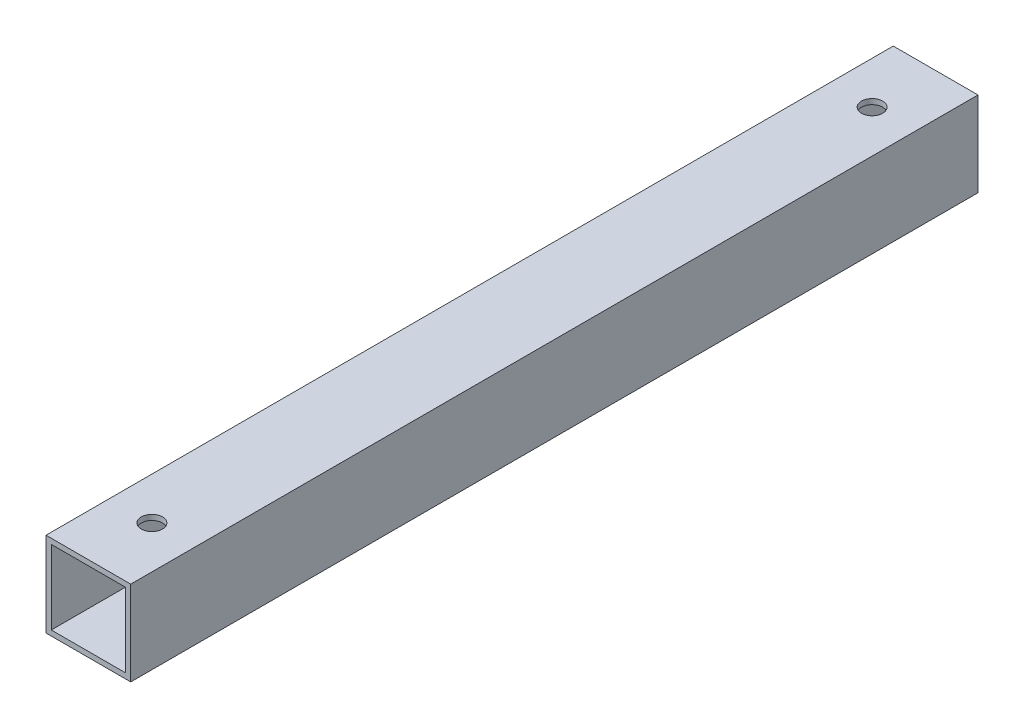
SolidWorks part; units mm, degrees
ref_plane "Front Plane" through (0, 0, 0) normal (0, 0, 1) x (1, 0, 0)
ref_plane "Top Plane" through (0, 0, 0) normal (0, 1, 0) x (1, 0, 0)
ref_plane "Right Plane" through (0, 0, 0) normal (1, 0, 0) x (0, 0, -1)
sketch "Sketch1" plane through (0, 0, 0) normal (0, 0, 1) x (1, 0, 0)
  line L1 (-11.1125, -11.1125) -> (11.1125, -11.1125)
  line L2 (-11.1125, -11.1125) -> (-11.1125, 11.1125)
  line L3 (-11.1125, 11.1125) -> (11.1125, 11.1125)
  line L4 (11.1125, -11.1125) -> (11.1125, 11.1125)
  line L5 (-11.1125, -11.1125) -> (11.1125, 11.1125) construction
  line L6 (-11.1125, 11.1125) -> (11.1125, -11.1125) construction
  line L7 (-12.7, -12.7) -> (12.7, -12.7)
  line L8 (-12.7, -12.7) -> (-12.7, 12.7)
  line L9 (-12.7, 12.7) -> (12.7, 12.7)
  line L10 (12.7, -12.7) -> (12.7, 12.7)
  line L11 (-12.7, -12.7) -> (12.7, 12.7) construction
  line L12 (-12.7, 12.7) -> (12.7, -12.7) construction
  point P0 (0, 0)
  point P6 (0, 0)
  dimension "D1" = 25.4
  dimension "D2" = 1.5875
extrude "Boss-Extrude1" add sketch "Sketch1" along normal blind 254
sketch "Sketch2" plane through (0, 12.7, 0) normal (0, 1, 0) x (1, 0, 0)
  line L0 (0, 0) -> (0, -19.05) construction
  line L1 (0, -19.05) -> (0, -234.95) construction
  line L2 (0, -234.95) -> (0, -254) construction
  line L3 (12.7, -254) -> (-12.7, -254) construction
  circle A0 centre (0, -19.05) radius 3.175
  circle A1 centre (0, -234.95) radius 3.175
  dimension "D1" = 6.35
  dimension "D2" = 19.05
extrude "Cut-Extrude1" cut sketch "Sketch2" against normal through all
